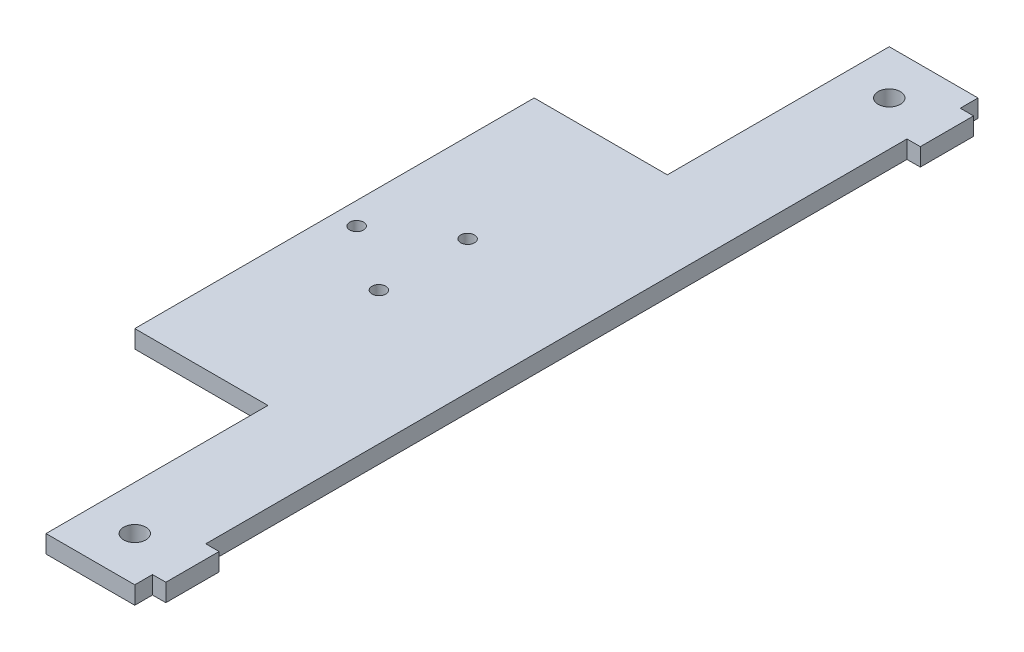
SolidWorks part; units mm, degrees
ref_plane "Alzado" through (0, 0, 0) normal (0, 0, 1) x (1, 0, 0)
ref_plane "Planta" through (0, 0, 0) normal (0, 1, 0) x (1, 0, 0)
ref_plane "Vista lateral" through (0, 0, 0) normal (1, 0, 0) x (0, 0, -1)
sketch "Croquis1" plane through (0, 0, 0) normal (0, 1, 0) x (1, 0, 0)
  line L0 (125, 40) -> (125, 0) construction
  line L1 (0, 0) -> (250, 0)
  line L2 (0, 0) -> (0, 250)
  line L3 (0, 250) -> (250, 250)
  line L4 (250, 0) -> (250, 250)
  line L5 (40, 40) -> (210, 40) construction
  line L6 (40, 40) -> (40, 210) construction
  line L7 (40, 210) -> (210, 210) construction
  line L8 (210, 40) -> (210, 210) construction
  line L9 (210, 125) -> (250, 125) construction
  circle A0 centre (40, 210) radius 2.5
  circle A1 centre (210, 210) radius 2.5
  circle A2 centre (210, 40) radius 2.5
  circle A3 centre (40, 40) radius 2.5
  dimension "D3" = 5
  dimension "D1" = 250
  dimension "D2" = 170
extrude "Saliente-Extruir1" add sketch "Croquis1" along normal blind 4
sketch "Croquis2" plane through (0, 4, 0) normal (0, 1, 0) x (1, 0, 0)
  line L0 (50, 125) -> (0, 125) construction
  line L1 (50, 50) -> (200, 50)
  line L2 (50, 50) -> (50, 150.0904)
  line L3 (50, 200) -> (200, 200)
  line L4 (200, 50) -> (200, 200)
  line L5 (0, 250) -> (0, 0) construction
  line L6 (125, 50) -> (125, 0) construction
  line L7 (0, 0) -> (250, 0) construction
  line L8 (50, 125) -> (200, 125) construction
  line L9 (125, 200) -> (125, 50) construction
  line L10 (48, 151.5) -> (48, 125) construction
  line L19 (50, 50) -> (200, 50) construction
  line L20 (50, 50) -> (50, 200) construction
  line L21 (50, 200) -> (200, 200) construction
  line L22 (200, 50) -> (200, 200) construction
  line L24 (50, 150.0904) -> (50, 172.9096)
  line L27 (59.9079, 125) -> (59.9079, 200) construction
  line L28 (50, 161.5) -> (34.9079, 161.5) construction
  line L29 (50, 150.0904) -> (125, 150.0904) construction
  line L30 (88.5, 200) -> (88.5, 125.0904) construction
  line L31 (78.5, 200) -> (98.5, 200)
  line L44 (121.5, 50) -> (101.5, 50)
  line L59 (88.5, 162.5452) -> (125, 162.5452) construction
  line L60 (42.454, 161.5) -> (42.454, 125) construction
  line L61 (25, 103.5) -> (25, 123.5) [skipped]
  line L65 (50, 150.0904) -> (50, 200)
  line L66 (125.0904, 175) -> (147.9096, 175) [skipped]
  line L69 (175, 146.5) -> (175, 126.5) [skipped]
  line L71 (150, 99.9096) -> (150, 77.0904) [skipped]
  line L72 (74.9096, 75) -> (52.0904, 75) [skipped]
  point P18 (50, 125)
  point P19 (125, 200)
  point P21 (0, 0)
  dimension "D1" = 150
  dimension "D2" = 150
  dimension "D4" = 4
  dimension "D6" = 36.5
extrude "Cortar-Extruir1" cut sketch "Croquis2" against normal blind 4
sketch "Croquis3" plane through (0, 4, 0) normal (0, 1, 0) x (1, 0, 0)
  line L0 (75, 175) -> (75, 75)
  line L1 (50, 200) -> (200, 200)
  line L2 (50, 200) -> (50, 50)
  line L3 (50, 50) -> (200, 50)
  line L4 (200, 200) -> (200, 50)
  line L5 (75, 75) -> (175, 75)
  line L6 (175, 175) -> (175, 75)
  line L7 (75, 175) -> (175, 175)
  dimension "D1" = 25
extrude "Saliente-Extruir2" add sketch "Croquis3" against normal up to surface (4 mm away) up to face at (125, 0, -125)
sketch "Croquis4" plane through (0, 4, 0) normal (0, 1, 0) x (1, 0, 0)
  line L0 (125, 0) -> (125, 75) construction
  line L1 (0, 0) -> (250, 0) construction
  line L2 (75, 75) -> (175, 75) construction
  line L3 (115, 20) -> (125, 20) construction
  line L4 (125, 20) -> (135, 20) construction
  circle A0 centre (115, 20) radius 1.55
  circle A1 centre (135, 20) radius 1.55
  circle A2 centre (125, 5) radius 1.55
  dimension "D1" = 3.1
  dimension "D4" = 5
  dimension "D2" = 10
  dimension "D3" = 20
extrude "Cortar-Extruir2" cut sketch "Croquis4" against normal blind 10
sketch "Croquis5" plane through (0, 4, 0) normal (0, 1, 0) x (1, 0, 0)
  line L0 (75, 175) -> (75, 75) construction
  line L1 (75, 75) -> (175, 75) construction
  line L2 (175, 75) -> (175, 175) construction
  line L3 (175, 175) -> (75, 175) construction
  line L4 (75, 175) -> (75, 75)
  line L5 (75, 75) -> (175, 75)
  line L6 (175, 75) -> (175, 175)
  line L7 (175, 175) -> (75, 175)
  line L8 (50, 200) -> (50, 50)
  line L9 (50, 50) -> (200, 50)
  line L10 (200, 50) -> (200, 200)
  line L11 (200, 200) -> (50, 200)
  dimension "D1" = 25
extrude "Cortar-Extruir3" cut sketch "Croquis5" against normal blind 10
sketch "Croquis6" plane through (0, 4, 0) normal (0, 1, 0) x (1, 0, 0)
  line L0 (250, 0) -> (250, 250) construction
  line L1 (250, 0) -> (170, 0)
  line L2 (250, 0) -> (250, 30)
  line L3 (250, 30) -> (170, 30)
  line L4 (170, 0) -> (170, 30)
  line L5 (220, 30) -> (250, 30)
  line L6 (220, 30) -> (220, 80)
  line L7 (220, 80) -> (250, 80)
  line L8 (250, 30) -> (250, 80)
  line L9 (50, 125) -> (200, 125) construction
  line L10 (50, 200) -> (50, 50) construction
  line L11 (200, 50) -> (200, 200) construction
  line L12 (125, 50) -> (125, 125) construction
  line L13 (50, 50) -> (200, 50) construction
  line L14 (0, 0) -> (30, 0)
  line L15 (0, 0) -> (0, 80)
  line L16 (0, 80) -> (30, 80)
  line L17 (30, 0) -> (30, 80)
  line L18 (30, 30) -> (80, 30)
  line L19 (30, 30) -> (30, 0)
  line L20 (30, 0) -> (80, 0)
  line L21 (80, 30) -> (80, 0)
  line L22 (0, 250) -> (0, 220)
  line L23 (0, 250) -> (80, 250)
  line L24 (80, 250) -> (80, 220)
  line L25 (0, 220) -> (80, 220)
  line L26 (30, 220) -> (30, 170)
  line L27 (30, 220) -> (0, 220)
  line L28 (0, 220) -> (0, 170)
  line L29 (30, 170) -> (0, 170)
  line L30 (250, 250) -> (220, 250)
  line L31 (250, 250) -> (250, 170)
  line L32 (250, 170) -> (220, 170)
  line L33 (220, 250) -> (220, 170)
  line L34 (220, 220) -> (170, 220)
  line L35 (220, 220) -> (220, 250)
  line L36 (220, 250) -> (170, 250)
  line L37 (170, 220) -> (170, 250)
  dimension "D1" = 30
  dimension "D2" = 80
  dimension "D3" = 80
  dimension "D4" = 4
extrude "Cortar-Extruir4" cut sketch "Croquis6" against normal blind 10 contours L2 L1 L4 L3 | L18 L21 L20 L19 | L14 L17 L16 L15 | L26 L29 L28 L27 | L22 L25 L24 L23 | L30 L33 L32 L31 | L34 L37 L36 L35 | L6 L5 L8 L7
sketch "Croquis8" plane through (0, 4, 0) normal (0, 1, 0) x (1, 0, 0)
  line L0 (50, 125) -> (200, 125) construction
  line L1 (50, 200) -> (50, 50) construction
  line L2 (200, 50) -> (200, 200) construction
  line L3 (125, 125) -> (125, 50) construction
  line L4 (50, 50) -> (200, 50) construction
  circle A0 centre (125, 5) radius 1.55 construction
  circle A1 centre (135, 20) radius 1.55 construction
  circle A2 centre (115, 20) radius 1.55 construction
  circle A3 centre (125, 5) radius 1.55
  circle A4 centre (135, 20) radius 1.55
  circle A5 centre (115, 20) radius 1.55
  circle A6 centre (20, 135) radius 1.55
  circle A7 centre (5, 125) radius 1.55
  circle A8 centre (20, 115) radius 1.55
  circle A9 centre (135, 230) radius 1.55
  circle A10 centre (125, 245) radius 1.55
  circle A11 centre (115, 230) radius 1.55
  circle A12 centre (230, 115) radius 1.55
  circle A13 centre (245, 125) radius 1.55
  circle A14 centre (230, 135) radius 1.55
  dimension "D1" = 4
extrude "Cortar-Extruir5" cut sketch "Croquis8" against normal blind 10
sketch "Croquis9" plane through (0, 4, 0) normal (0, 1, 0) x (1, 0, 0)
  line L0 (250, 80) -> (250, 170) construction
  line L1 (50, 0) -> (250, 0)
  line L2 (50, 0) -> (50, 34)
  line L3 (50, 250) -> (250, 250)
  line L4 (250, 0) -> (250, 250)
  line L5 (170, 250) -> (80, 250) construction
  line L7 (80, 0) -> (170, 0) construction
  line L8 (50, 200) -> (50, 50) construction
  line L9 (40, 40) -> (53, 40) construction
  line L10 (50, 46) -> (53, 46)
  line L12 (50, 34) -> (53, 34)
  line L13 (53, 46) -> (53, 34)
  line L14 (50, 46) -> (50, 204)
  line L15 (0, 125) -> (250, 125) construction
  line L16 (0, 170) -> (0, 80) construction
  line L17 (50, 216) -> (53, 216)
  line L18 (53, 204) -> (53, 216)
  line L19 (50, 204) -> (53, 204)
  line L20 (50, 216) -> (50, 250)
  dimension "D1" = 12
  dimension "D2" = 3
extrude "Cortar-Extruir6" cut sketch "Croquis9" against normal blind 10
